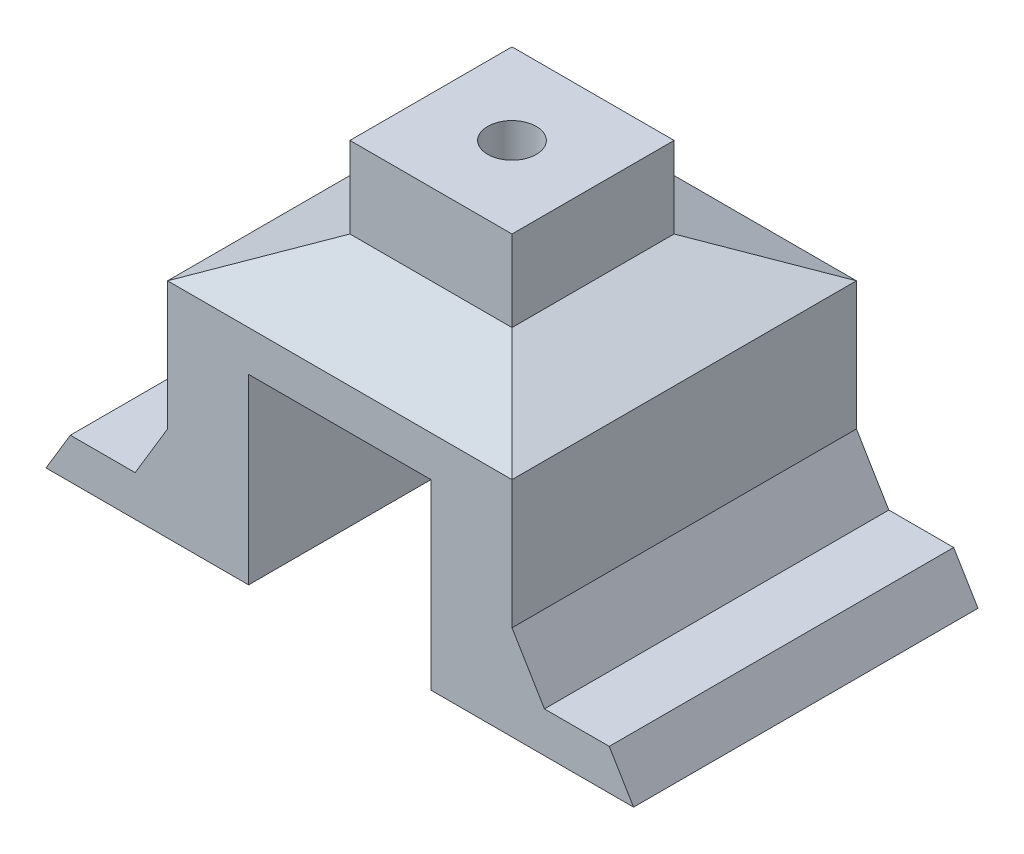
SolidWorks part; units mm, degrees
ref_plane "Top Plane" through (0, 0, 0) normal (0, 0, 1) x (1, 0, 0)
ref_plane "Right Plane" through (0, 0, 0) normal (0, 1, 0) x (1, 0, 0)
ref_plane "Front Plane" through (0, 0, 0) normal (1, 0, 0) x (0, 0, -1)
sketch "Sketch1" plane through (0, 0, 0) normal (0, 0, 1) x (1, 0, 0)
  line L0 (-11.25, 0) -> (-11.25, 22.5)
  line L1 (-11.25, 22.5) -> (11.25, 22.5)
  line L2 (11.25, 22.5) -> (11.25, 0)
  line L3 (11.25, 0) -> (36.25, 0)
  line L4 (36.25, 0) -> (33.25, 5)
  line L5 (33.25, 5) -> (25.25, 5)
  line L6 (21.25, 11.6667) -> (21.25, 27.5)
  line L7 (21.25, 27.5) -> (10, 32.5)
  line L8 (10, 32.5) -> (10, 42.5)
  line L9 (10, 42.5) -> (-10, 42.5)
  line L10 (-10, 42.5) -> (-10, 32.5)
  line L11 (-10, 32.5) -> (-21.25, 27.5)
  line L12 (-21.25, 27.5) -> (-21.25, 11.6667)
  line L13 (-25.25, 5) -> (-33.25, 5)
  line L14 (-33.25, 5) -> (-36.25, 0)
  line L15 (-36.25, 0) -> (-11.25, 0)
  line L16 (0, 22.5) -> (0, 0) construction
  line L17 (0, 22.5) -> (0, 42.5) construction
  line L18 (-10, 32.5) -> (10, 32.5) construction
  line L19 (-25.25, 5) -> (-21.25, 11.6667)
  line L20 (-21.25, 5) -> (-25.25, 5) construction
  line L21 (21.25, 11.6667) -> (25.25, 5)
  line L22 (-21.25, 11.6667) -> (-21.25, 5) construction
  line L23 (21.25, 5) -> (21.25, 11.6667) construction
  line L24 (25.25, 5) -> (21.25, 5) construction
  point P10 (16.1373, 5)
  point P24 (15.5169, 5)
  point P25 (13.6558, 5)
  dimension "D1" = 22.5
  dimension "D2" = 25
  dimension "D3" = 5
  dimension "D4" = 3
  dimension "D5" = 10
  dimension "D6" = 5
  dimension "D7" = 20
  dimension "D8" = 20
  dimension "D9" = 10
  dimension "D10" = 4
extrude "Boss-Extrude1" add sketch "Sketch1" along normal mid plane 42.5
sketch "Sketch2" plane through (0, 0, 0) normal (1, 0, 0) x (0, 0, -1)
  line L0 (21.25, 27.5) -> (10, 32.5)
  line L1 (10, 32.5) -> (10, 42.5)
  line L2 (10, 42.5) -> (-10, 42.5) construction
  line L3 (-10, 42.5) -> (-10, 32.5)
  line L4 (-10, 32.5) -> (-21.25, 27.5)
  line L5 (-21.25, 27.5) -> (-21.25, 42.5)
  line L7 (21.25, 42.5) -> (10, 42.5)
  line L8 (-10, 42.5) -> (-21.25, 42.5)
  line L9 (-21.25, 42.5) -> (21.25, 42.5) construction
  line L11 (21.25, 27.5) -> (21.25, 42.5)
  line L12 (-21.25, 32.5) -> (21.25, 32.5) construction
  point P8 (17, 27.5)
  point P9 (0, 42.5)
  point P12 (0, 0)
  point P16 (-5.6499, 32.5)
  point P17 (0, 0)
  dimension "D1" = 20
extrude "Cut-Extrude1" cut sketch "Sketch2" against normal through all both and the other way through all
sketch "Sketch3" plane through (0, 42.5, 0) normal (0, 1, 0) x (1, 0, 0)
  circle A0 centre (0, 0) radius 3
  dimension "D1" = 6
extrude "Cut-Extrude2" cut sketch "Sketch3" against normal through all
